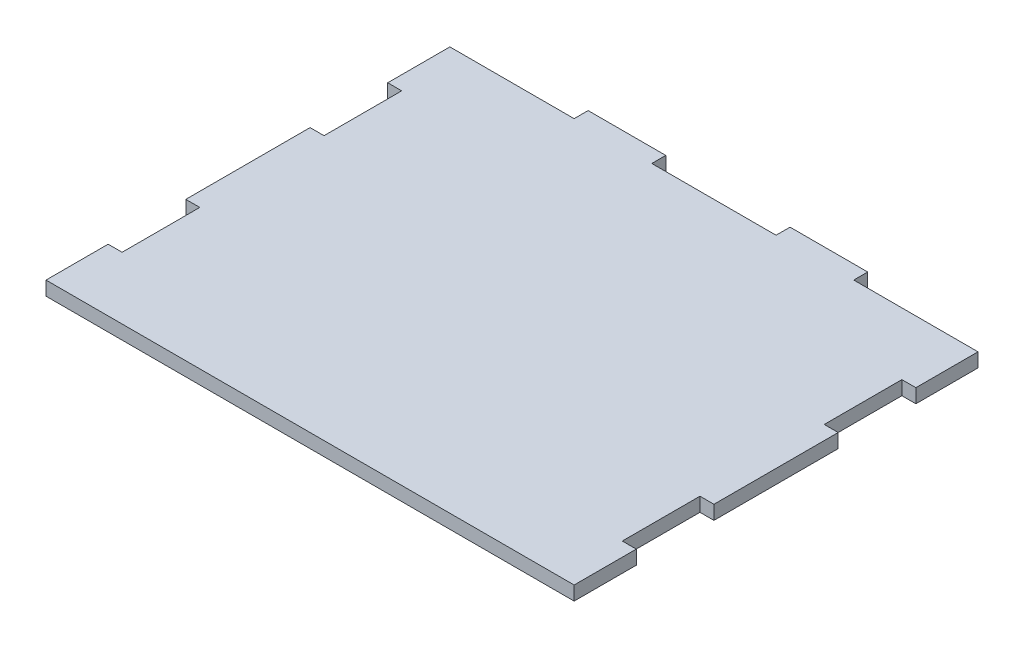
SolidWorks part; units mm, degrees
ref_plane "Front Plane" through (0, 0, 0) normal (0, 0, 1) x (1, 0, 0)
ref_plane "Top Plane" through (0, 0, 0) normal (0, 1, 0) x (1, 0, 0)
ref_plane "Right Plane" through (0, 0, 0) normal (1, 0, 0) x (0, 0, -1)
sketch "Sketch1" plane through (0, 0, 0) normal (0, 1, 0) x (1, 0, 0)
  line L0 (-6.4466, 35.6952) -> (-6.4466, -94.3048) construction
  line L1 (-91.4466, 35.6952) -> (-51.4466, 35.6952)
  line L2 (-91.4466, 35.6952) -> (-91.4466, 15.6952)
  line L3 (-91.4466, -94.3048) -> (78.5534, -94.3048)
  line L4 (78.5534, 35.6952) -> (78.5534, 15.6952)
  line L5 (-91.4466, -29.3048) -> (78.5534, -29.3048) construction
  line L6 (38.5534, 40.1952) -> (13.5534, 40.1952)
  line L8 (-51.4466, 35.6952) -> (-51.4466, 40.1952)
  line L9 (-51.4466, 40.1952) -> (-26.4466, 40.1952)
  line L10 (-26.4466, 35.6952) -> (-26.4466, 40.1952)
  line L15 (-91.4466, 15.6952) -> (-86.9466, 15.6952)
  line L17 (-91.4466, -9.3048) -> (-86.9466, -9.3048)
  line L18 (-86.9466, 15.6952) -> (-86.9466, -9.3048)
  line L19 (13.5534, 35.6952) -> (13.5534, 40.1952)
  line L21 (38.5534, 35.6952) -> (38.5534, 40.1952)
  line L22 (-91.4466, -49.3048) -> (-86.9466, -49.3048)
  line L23 (-86.9466, -74.3048) -> (-86.9466, -49.3048)
  line L24 (-91.4466, -74.3048) -> (-86.9466, -74.3048)
  line L27 (78.5534, -74.3048) -> (74.0534, -74.3048)
  line L28 (74.0534, -74.3048) -> (74.0534, -49.3048)
  line L29 (78.5534, -49.3048) -> (74.0534, -49.3048)
  line L30 (78.5534, -9.3048) -> (74.0534, -9.3048)
  line L31 (74.0534, 15.6952) -> (74.0534, -9.3048)
  line L32 (78.5534, 15.6952) -> (74.0534, 15.6952)
  line L34 (-91.4466, -9.3048) -> (-91.4466, -49.3048)
  line L35 (-91.4466, -74.3048) -> (-91.4466, -94.3048)
  line L36 (-26.4466, 35.6952) -> (13.5534, 35.6952)
  line L37 (38.5534, 35.6952) -> (78.5534, 35.6952)
  line L38 (78.5534, -9.3048) -> (78.5534, -49.3048)
  line L39 (78.5534, -74.3048) -> (78.5534, -94.3048)
  dimension "D1" = 170
  dimension "D2" = 130
  dimension "D3" = 4.5
  dimension "D4" = 25
  dimension "D5" = 40
  dimension "D6" = 4.5
  dimension "D7" = 25
  dimension "D8" = 20
extrude "Boss-Extrude1" add sketch "Sketch1" along normal blind 4.5
